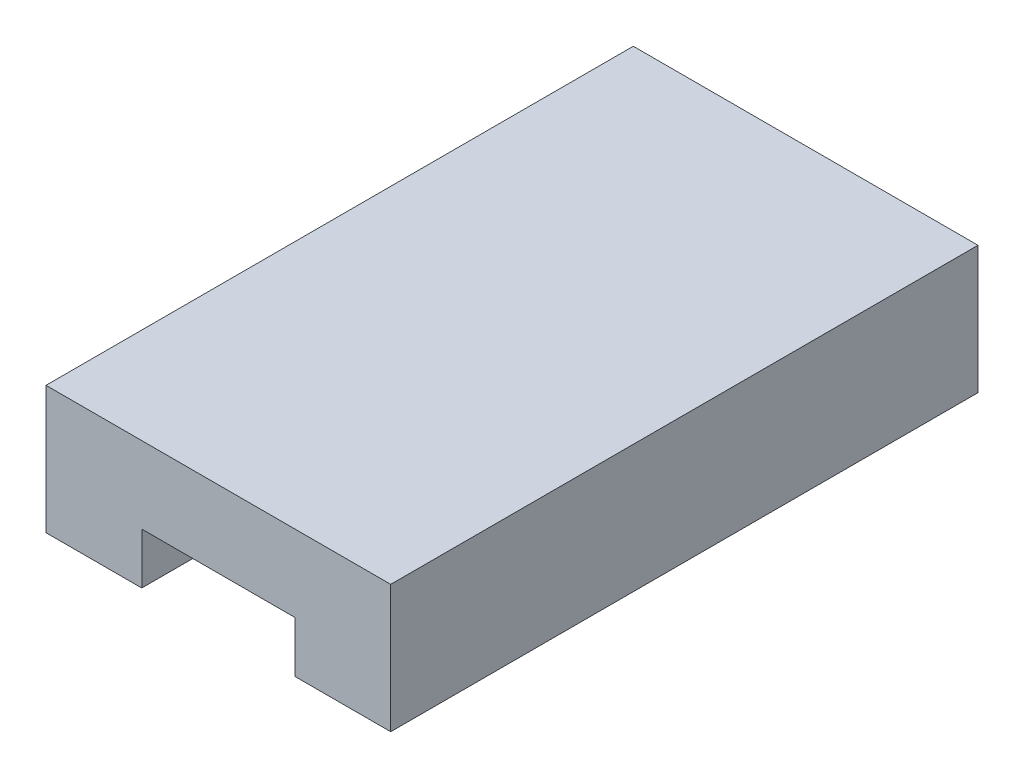
SolidWorks part; units mm, degrees
ref_plane "Front Plane" through (0, 0, 0) normal (0, 0, 1) x (1, 0, 0)
ref_plane "Top Plane" through (0, 0, 0) normal (0, 1, 0) x (1, 0, 0)
ref_plane "Right Plane" through (0, 0, 0) normal (1, 0, 0) x (0, 0, -1)
sketch "Sketch1" plane through (0, 0, 0) normal (0, 0, 1) x (1, 0, 0)
  line L0 (19.5, 0) -> (27, 0)
  line L1 (0, 0) -> (7.5, 0)
  line L2 (0, 0) -> (0, 10)
  line L3 (0, 10) -> (27, 10)
  line L4 (27, 0) -> (27, 10)
  line L6 (7.5, 0) -> (7.5, 4)
  line L7 (7.5, 4) -> (19.5, 4)
  line L8 (19.5, 0) -> (19.5, 4)
  point P9 (13.5, 4)
  point P10 (13.5, 10)
  dimension "D1" = 12
  dimension "D2" = 10
  dimension "D3" = 4
  dimension "D4" = 27
extrude "Boss-Extrude1" add sketch "Sketch1" along normal blind 46
